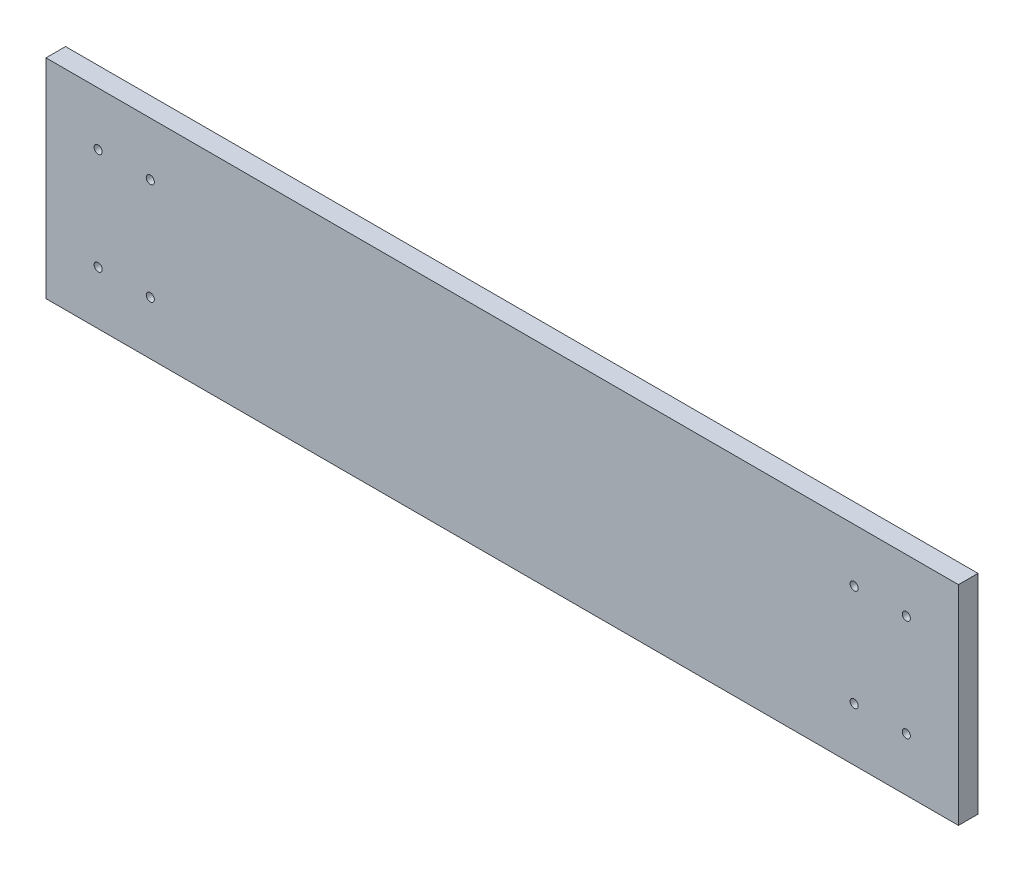
SolidWorks part; units mm, degrees
material "Balsa"
ref_plane "Front Plane" through (0, 0, 0) normal (0, 0, 1) x (1, 0, 0)
ref_plane "Top Plane" through (0, 0, 0) normal (0, 1, 0) x (1, 0, 0)
ref_plane "Right Plane" through (0, 0, 0) normal (1, 0, 0) x (0, 0, -1)
sketch "Sketch1" plane through (0, 0, 0) normal (0, 0, 1) x (1, 0, 0)
  line L1 (0, 0) -> (889, 0)
  line L2 (0, 0) -> (0, 203.2)
  line L3 (0, 203.2) -> (889, 203.2)
  line L4 (889, 0) -> (889, 203.2)
  dimension "D1" = 889
  dimension "D2" = 203.2
extrude "Boss-Extrude1" add sketch "Sketch1" along normal blind 19.05
sketch "Esquisse1" plane through (0, 0, 0) normal (0, 0, -1) x (-1, 0, 0)
  line L0 (-889, 203.2) -> (0, 203.2) construction
  line L1 (-889, 0) -> (-889, 203.2) construction
  line L2 (0, 203.2) -> (0, 0) construction
  circle A0 centre (-838.2, 151.2) radius 3.937
  circle A1 centre (-787.4, 151.2) radius 3.937
  circle A2 centre (-787.4, 52) radius 3.937
  circle A3 centre (-838.2, 52) radius 3.937
  circle A4 centre (-101.6, 151.2) radius 3.937
  circle A5 centre (-50.8, 151.2) radius 3.937
  circle A6 centre (-50.8, 52) radius 3.937
  circle A7 centre (-101.6, 52) radius 3.937
  dimension "D1" = 7.874
  dimension "D2" = 50.8
  dimension "D3" = 50.8
  dimension "D4" = 99.2
  dimension "D5" = 99.2
  dimension "D6" = 52
  dimension "D7" = 50.8
  dimension "D8" = 50.8
  dimension "D9" = 111.4508
  dimension "D10" = 50.8
  dimension "D11" = 50.8
  dimension "D12" = 50.8
  dimension "D13" = 111.4508
  dimension "D14" = 111.4508
  dimension "D15" = 99.2
  dimension "D16" = 52
  dimension "D17" = 72.6955
extrude "Enlèv. mat.-Extru.1" cut sketch "Esquisse1" against normal through all
